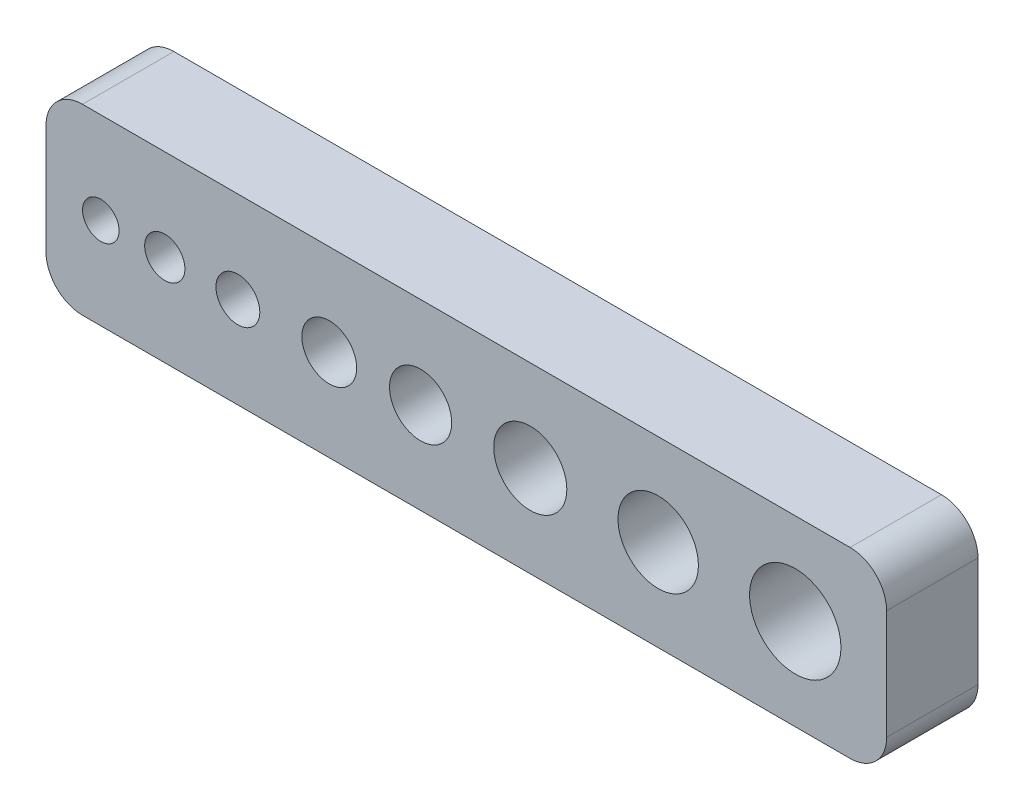
SolidWorks part; units mm, degrees
ref_plane "Front Plane" through (0, 0, 0) normal (0, 0, 1) x (1, 0, 0)
ref_plane "Top Plane" through (0, 0, 0) normal (0, 1, 0) x (1, 0, 0)
ref_plane "Right Plane" through (0, 0, 0) normal (1, 0, 0) x (0, 0, -1)
sketch "Sketch1" plane through (0, 0, 0) normal (0, 0, 1) x (1, 0, 0)
  line L0 (-4, 0) -> (3, 0) construction
  line L1 (55, 0) -> (-55, 0) construction
  line L2 (3, 0) -> (10.5, 0) construction
  line L7 (-4, 0) -> (-10, 0) construction
  line L8 (-10, 0) -> (-15, 0) construction
  line L9 (-20, 0) -> (-24, 0) construction
  line L10 (-15, 0) -> (-20, 0) construction
  line L12 (-24, 0) -> (-27.5, 0) construction
  line L13 (-30.5, -3) -> (-30.5, 3)
  line L14 (-28.5, 5) -> (13.5, 5)
  line L15 (15.5, 3) -> (15.5, -3)
  line L16 (-28.5, -5) -> (13.5, -5)
  circle A0 centre (-4, 0) radius 2
  circle A1 centre (3, 0) radius 2.2
  circle A2 centre (10.5, 0) radius 2.5
  circle A7 centre (-10, 0) radius 1.7
  circle A8 centre (-15, 0) radius 1.5
  circle A9 centre (-20, 0) radius 1.2
  circle A10 centre (-24, 0) radius 1.1
  circle A11 centre (-27.5, 0) radius 1
  arc A12 (-28.5, 5) -> (-30.5, 3) centre (-28.5, 3) ccw
  arc A13 (-28.5, -5) -> (-30.5, -3) centre (-28.5, -3) cw
  arc A14 (13.5, -5) -> (15.5, -3) centre (13.5, -3) ccw
  arc A15 (15.5, 3) -> (13.5, 5) centre (13.5, 3) ccw
  point P14 (25, 0)
  point P15 (-5, 0)
  point P17 (25, -5)
  point P20 (25, 5)
  point P23 (-5, -5)
  point P26 (-5, 5)
  point P30 (15.5, 0)
  point P33 (-30.5, 5)
  point P36 (-30.5, -5)
  point P39 (15.5, -5)
  point P42 (15.5, 5)
  dimension "D1" = 2
  dimension "D2" = 2
extrude "Boss-Extrude1" add sketch "Sketch1" along normal blind 5
